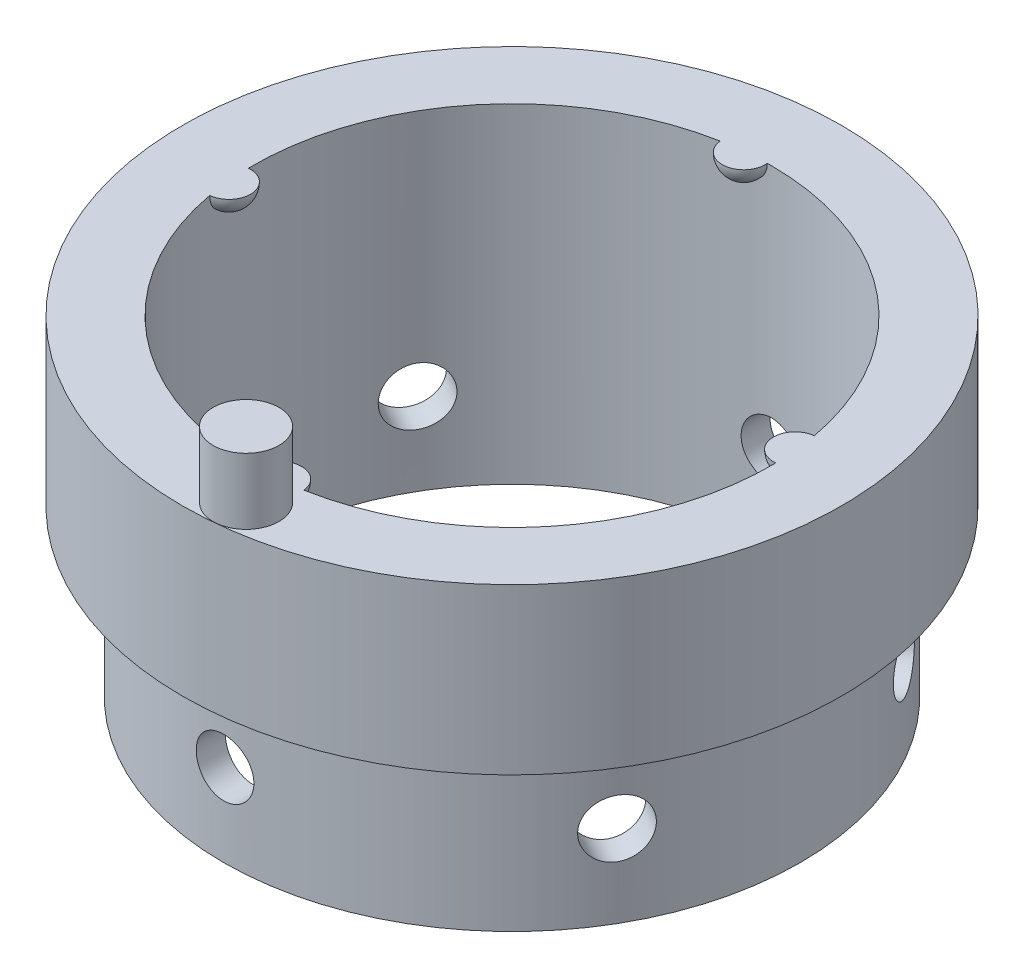
SolidWorks part; units mm, degrees
ref_plane "Front Plane" through (0, 0, 0) normal (0, 0, 1) x (1, 0, 0)
ref_plane "Top Plane" through (0, 0, 0) normal (0, 1, 0) x (1, 0, 0)
ref_plane "Right Plane" through (0, 0, 0) normal (1, 0, 0) x (0, 0, -1)
sketch "Sketch1" plane through (0, 0, 0) normal (1, 0, 0) x (0, 0, -1)
  line L0 (0, 0) -> (0, -25.4)
  line L1 (0, -25.4) -> (6.35, -25.4)
  line L2 (6.35, -25.4) -> (6.35, -50.8)
  line L3 (6.35, -50.8) -> (12.7, -50.8)
  line L4 (12.7, -50.8) -> (12.7, 0)
  line L5 (12.7, 0) -> (0, 0)
  line L6 (50.8, 24.6683) -> (50.8, -68.1514) construction
  dimension "D1" = 50.8
  dimension "D2" = 25.4
  dimension "D3" = 12.7
  dimension "D5" = 50.8
  dimension "D6" = 6.35
revolve "Revolve1" add sketch "Sketch1" angle 360 about L6
sketch3d "3DSketch1"
  point P0 (10.0592, -39.2736, -7.5032)
sketch3d "3DSketch2"
  point P0 (-5.746, -39.589, -6.7229)
sketch3d "3DSketch3"
  point P0 (5.6287, -43.1069, -6.7078)
ref_plane "Plane4" through (0, 0, -6.7078) normal (0, 0, 1) x (1, 0, 0)
sketch "Sketch8" plane through (0, 0, -6.7078) normal (0, 0, 1) x (1, 0, 0)
  line L0 (-44.45, -50.8) -> (44.45, -50.8) construction
  circle A0 centre (0, -38.1) radius 4.445
  dimension "D1" = 12.7
  dimension "D2" = 8.89
extrude "Cut-Extrude2" cut sketch "Sketch8" against normal mid plane 20.32
pattern_circular "CirPattern1" count 6 over 360 about axis through (0, 24.6683, -50.8) along (0, 1, 0) of "Cut-Extrude2"
sketch "Sketch10" plane through (0, -50.8, 0) normal (0, -1, 0) x (1, 0, 0)
  circle A0 centre (0, -50.8) radius 40.005
  dimension "D1" = 80.01
extrude "Cut-Extrude4" cut sketch "Sketch10" against normal through all
sketch3d "3DSketch4"
  line L0 (-20.2685, 0, -16.3096) -> (-20.2685, -50.8, -16.3096) construction
  circle A0 centre (0, 0, -50.8) radius 40.005 construction
  circle A1 centre (0, -50.8, -50.8) radius 40.005 construction
  point P4 (0, -40.005, -50.8)
  point P7 (0, -90.805, -50.8)
sketch "Sketch14" plane through (0, 0, 0) normal (0, 1, 0) x (1, 0, 0)
  line L0 (0.6498, 10.8003) -> (7.2538, 11.4581) construction
  line L1 (7.2538, 11.4581) -> (0.6498, 10.8003)
  arc A0 (7.2538, 11.4581) -> (0.6498, 10.8003) centre (3.9518, 11.1292) ccw
  circle A1 centre (0, 50.8) radius 40.005 construction
  dimension "D1" = 6.604
sketch "Sketch15" plane through (0, 0, 0) normal (0, 1, 0) x (1, 0, 0)
  line L0 (0.6498, 10.8003) -> (7.2538, 11.4581)
revolve "Revolve4" add sketch "Sketch14" angle 180 about L0
pattern_circular "CirPattern2" count 4 over 360 about axis through (0, 0, -50.8) along (0, 1, 0) of "Revolve4"
sketch "Sketch16" plane through (0, 0, 0) normal (0, 1, 0) x (1, 0, 0)
  circle A0 centre (4.4526, 5.3502) radius 5.0793
extrude "Boss-Extrude1" add sketch "Sketch16" along normal blind 10.16
